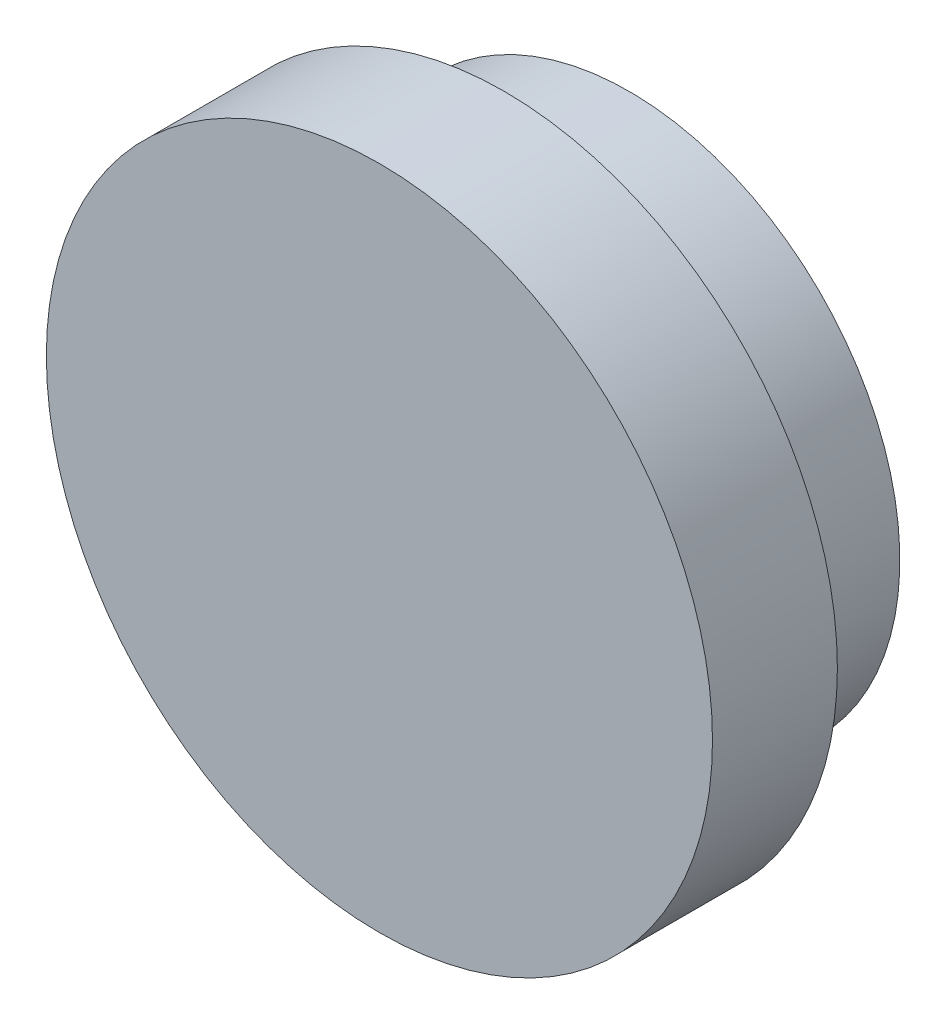
SolidWorks part; units mm, degrees
material "6061 Alloy"
ref_plane "Front Plane" through (0, 0, 0) normal (0, 0, 1) x (1, 0, 0)
ref_plane "Top Plane" through (0, 0, 0) normal (0, 1, 0) x (1, 0, 0)
ref_plane "Right Plane" through (0, 0, 0) normal (1, 0, 0) x (0, 0, -1)
sketch "Sketch1" plane through (0, 0, 0) normal (1, 0, 0) x (0, 0, -1)
  line L0 (0, 8) -> (3, 8)
  line L1 (0, 9.35) -> (0, -9.35) construction
  line L2 (3, 8) -> (3, 6.5)
  line L3 (3, 6.5) -> (6, 6.5)
  line L4 (6, 6.5) -> (6, 0)
  line L5 (3.3, 0) -> (-3.3, 0) construction
  line L6 (6, 0) -> (0, 0)
  line L7 (0, 0) -> (0, 8)
  dimension "D1" = 3
  dimension "D2" = 3
  dimension "D3" = 1.5
  dimension "D4" = 6.5
revolve "Revolve1" add sketch "Sketch1" angle 360 about L6
